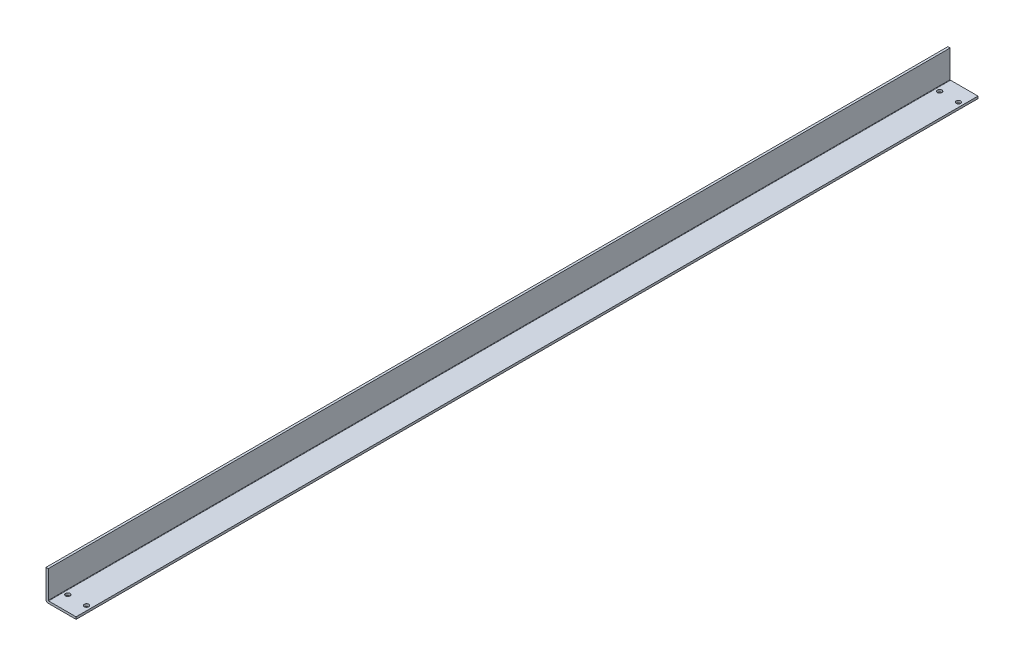
SolidWorks part; units mm, degrees
ref_plane "Front" through (0, 0, 0) normal (0, 0, 1) x (1, 0, 0)
ref_plane "Top" through (0, 0, 0) normal (0, 1, 0) x (1, 0, 0)
ref_plane "Right" through (0, 0, 0) normal (1, 0, 0) x (0, 0, -1)
sketch "Sketch1" plane through (0, 0, 0) normal (0, 0, 1) x (1, 0, 0)
  line L0 (0, 3) -> (0, 40)
  line L1 (0, 40) -> (3, 40)
  line L2 (3, 40) -> (3, 3.5)
  line L3 (3.5, 3) -> (40, 3)
  line L4 (40, 3) -> (40, 0)
  line L5 (40, 0) -> (3, 0)
  arc A0 (0, 3) -> (3, 0) centre (3, 3) ccw
  arc A1 (3, 3.5) -> (3.5, 3) centre (3.5, 3.5) ccw
  point P9 (0, 0)
  dimension "D5" = 3
  dimension "D6" = 0.5
  dimension "D1" = 40
  dimension "D2" = 40
  dimension "D3" = 3
  dimension "D4" = 3
extrude "Boss-Extrude1" add sketch "Sketch1" along normal blind 1200
sketch "Sketch2" plane through (0, 3, 0) normal (0, 1, 0) x (1, 0, 0)
  line L0 (40, -1200) -> (3.5, -1200) construction
  line L1 (0, -1200) -> (0, 0) construction
  line L2 (40, 0) -> (3.5, 0) construction
  line L3 (3.5, -1200) -> (3.5, 0) construction
  circle A0 centre (9, -1180) radius 3
  circle A1 centre (34, -1180) radius 3
  circle A2 centre (9, -20) radius 3
  circle A3 centre (34, -20) radius 3
  point P14 (0, 0)
  dimension "D1" = 6
  dimension "D4" = 6
  dimension "D9" = 6
  dimension "D10" = 6
  dimension "D2" = 20
  dimension "D3" = 9
  dimension "D5" = 25
  dimension "D6" = 9
  dimension "D7" = 25
  dimension "D8" = 20
extrude "Cut-Extrude1" cut sketch "Sketch2" against normal up to next
